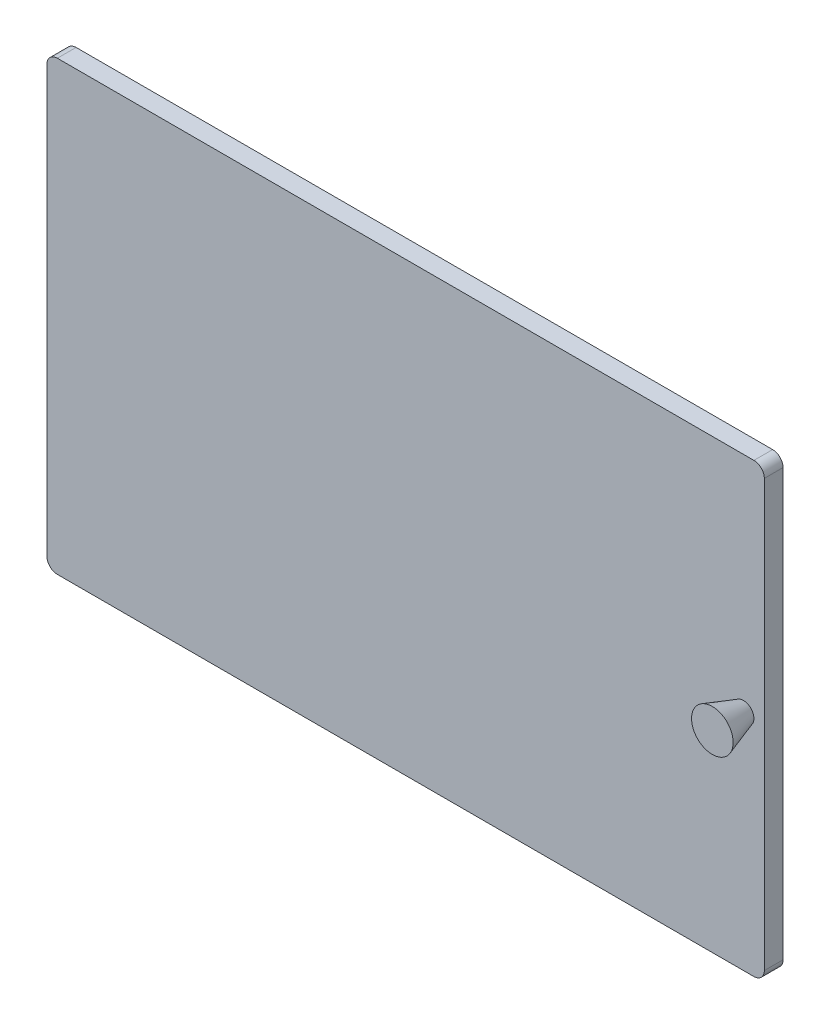
SolidWorks part; units mm, degrees
ref_plane "Front Plane" through (0, 0, 0) normal (0, 0, 1) x (1, 0, 0)
ref_plane "Top Plane" through (0, 0, 0) normal (0, 1, 0) x (1, 0, 0)
ref_plane "Right Plane" through (0, 0, 0) normal (1, 0, 0) x (0, 0, -1)
sketch "Sketch1" plane through (0, 0, 0) normal (0, 0, 1) x (1, 0, 0)
  line L1 (-33.5, -21.5) -> (33.5, -21.5)
  line L2 (-34.5, -20.5) -> (-34.5, 20.5)
  line L3 (-33.5, 21.5) -> (33.5, 21.5)
  line L4 (34.5, -20.5) -> (34.5, 20.5)
  line L5 (-34.5, -21.5) -> (34.5, 21.5) construction
  line L6 (-34.5, 21.5) -> (34.5, -21.5) construction
  arc A0 (33.5, -21.5) -> (34.5, -20.5) centre (33.5, -20.5) ccw
  arc A1 (-33.5, -21.5) -> (-34.5, -20.5) centre (-33.5, -20.5) cw
  arc A2 (33.5, 21.5) -> (34.5, 20.5) centre (33.5, 20.5) cw
  arc A3 (-34.5, 20.5) -> (-33.5, 21.5) centre (-33.5, 20.5) cw
  point P0 (0, 0)
  dimension "D3" = 1
  dimension "D1" = 69
  dimension "D2" = 43
extrude "Boss-Extrude1" add sketch "Sketch1" along normal blind 1.8
sketch "Sketch2" plane through (0, 0, 1.8) normal (0, 0, 1) x (1, 0, 0)
  line L0 (-34.5, 0) -> (34.5, 0) construction
  line L1 (-34.5, 20.5) -> (-34.5, -20.5) construction
  line L2 (34.5, -20.5) -> (34.5, 20.5) construction
  line L3 (30.5, 21.5) -> (30.5, -21.5) construction
  line L4 (33.5, 21.5) -> (-33.5, 21.5) construction
  line L5 (-33.5, -21.5) -> (33.5, -21.5) construction
  line L6 (32.5, 21.5) -> (32.5, -21.5) construction
  circle A0 centre (32.5, 0) radius 1
  dimension "D3" = 2
  dimension "D1" = 2
  dimension "D2" = 2
extrude "Boss-Extrude2" add sketch "Sketch2" along normal blind 3 draft 18.434 draft outward yes
